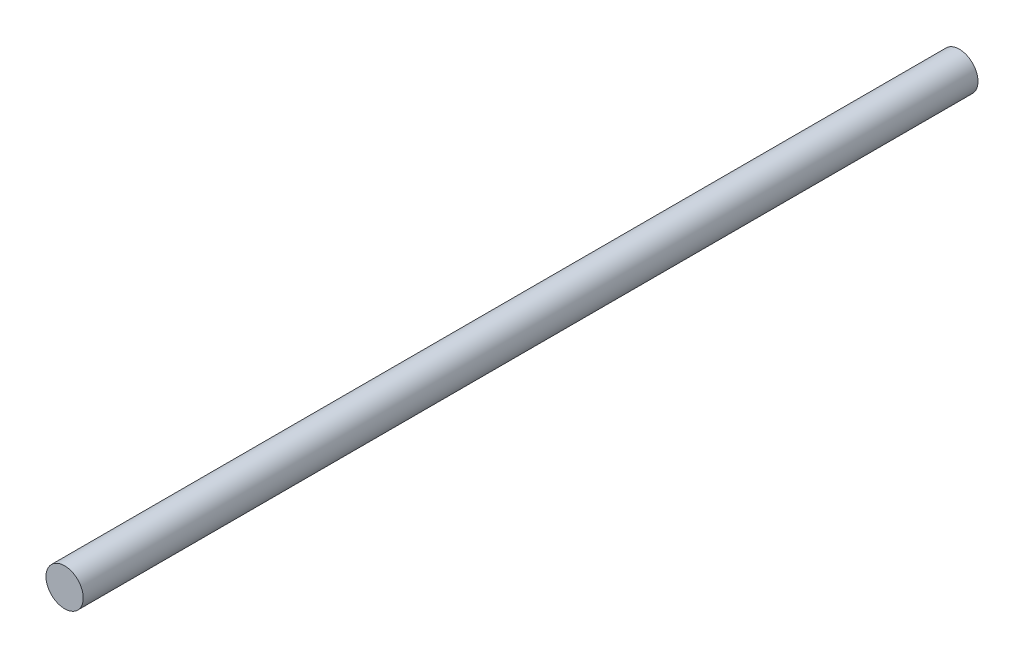
SolidWorks part; units mm, degrees
ref_plane "Front Plane" through (0, 0, 0) normal (0, 0, 1) x (1, 0, 0)
ref_plane "Top Plane" through (0, 0, 0) normal (0, 1, 0) x (1, 0, 0)
ref_plane "Right Plane" through (0, 0, 0) normal (1, 0, 0) x (0, 0, -1)
sketch "Sketch1" plane through (0, 0, 0) normal (0, 0, 1) x (1, 0, 0)
  circle A0 centre (0, 0) radius 2.5
extrude "Boss-Extrude1" add sketch "Sketch1" along normal blind 120
ref_plane "Plane1" through (0, 0, 104) normal (0, 0, 1) x (1, 0, 0)
sketch "Sketch2" plane through (0, 0, 104) normal (0, 0, 1) x (1, 0, 0)
  circle A0 centre (0, 0) radius 2.5
